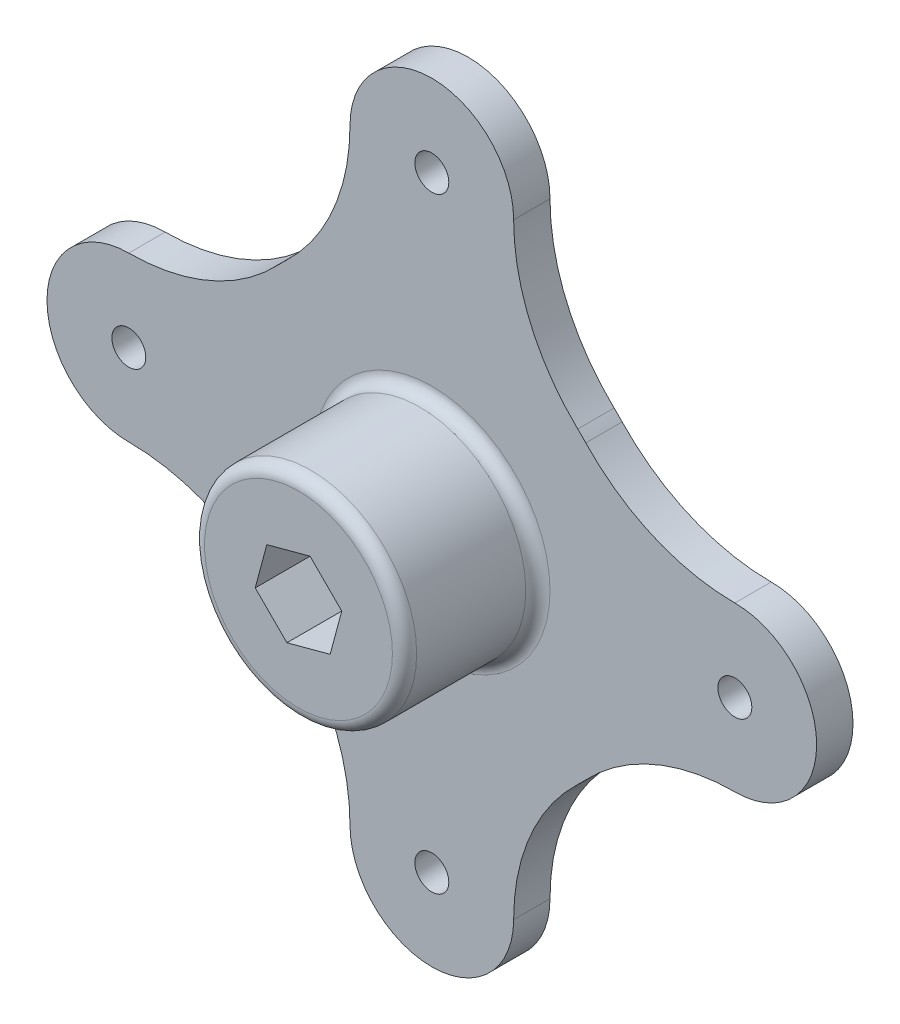
SolidWorks part; units mm, degrees
ref_plane "Front Plane" through (0, 0, 0) normal (0, 0, 1) x (1, 0, 0)
ref_plane "Top Plane" through (0, 0, 0) normal (0, 1, 0) x (1, 0, 0)
ref_plane "Right Plane" through (0, 0, 0) normal (1, 0, 0) x (0, 0, -1)
sketch "Sketch1" plane through (0, 0, 0) normal (0, 0, 1) x (1, 0, 0)
  line L0 (0, 0) -> (9.439, 9.439) construction
  line L1 (2.6128, -2.6128) -> (3.5691, 0.9563)
  line L2 (3.5691, 0.9563) -> (0.9563, 3.5691)
  line L3 (0.9563, 3.5691) -> (-2.6128, 2.6128)
  line L4 (-2.6128, 2.6128) -> (-3.5691, -0.9563)
  line L5 (-3.5691, -0.9563) -> (-0.9563, -3.5691)
  line L6 (-0.9563, -3.5691) -> (2.6128, -2.6128)
  line L7 (0, 0) -> (10.3087, 0) construction
  circle A0 centre (0, 0) radius 3.2 construction
  point P1 (1.8475, 3.2)
  point P11 (0, 0)
  point P12 (2.9055, -2.2829)
  dimension "D1" = 6.4
  dimension "D2" = 45
sketch "Sketch2" plane through (0, 0, 0) normal (0, 0, 1) x (1, 0, 0)
  circle A0 centre (0, 0) radius 8.75
  dimension "D1" = 17.5
extrude "Boss-Extrude1" add sketch "Sketch2" along normal blind 14
sketch "Sketch3" plane through (0, 0, 0) normal (0, 0, 1) x (1, 0, 0)
  circle A0 centre (0, 25) radius 1.4
  arc A1 (6.75, 25) -> (-6.75, 25) centre (0, 25) ccw
  circle A2 centre (0, 0) radius 17.5 construction
  arc A3 (-6.75, 25) -> (-12.0384, 12.7015) centre (-23.6948, 25) cw
  arc A4 (6.75, 25) -> (12.0384, 12.7015) centre (23.6948, 25) ccw
  arc A5 (-6.75, 25) -> (6.75, 25) centre (0, 25) ccw construction
  arc A6 (-25, 6.75) -> (-12.7015, 12.0384) centre (-25, 23.6948) ccw
  circle A7 centre (-25, 0) radius 1.4
  arc A8 (-25, 6.75) -> (-25, -6.75) centre (-25, 0) ccw
  arc A9 (-25, -6.75) -> (-12.7015, -12.0384) centre (-25, -23.6948) cw
  arc A10 (-6.75, -25) -> (-12.0384, -12.7015) centre (-23.6948, -25) ccw
  circle A11 centre (0, -25) radius 1.4
  arc A12 (-6.75, -25) -> (6.75, -25) centre (0, -25) ccw
  arc A13 (6.75, -25) -> (12.0384, -12.7015) centre (23.6948, -25) cw
  arc A14 (25, -6.75) -> (12.7015, -12.0384) centre (25, -23.6948) ccw
  circle A15 centre (25, 0) radius 1.4
  arc A16 (25, -6.75) -> (25, 6.75) centre (25, 0) ccw
  arc A17 (25, 6.75) -> (12.7015, 12.0384) centre (25, 23.6948) cw
  arc A18 (-12.7015, 12.0384) -> (-12.0384, 12.7015) centre (0, 0) cw
  arc A19 (12.0384, 12.7015) -> (12.7015, 12.0384) centre (0, 0) cw
  arc A20 (12.7015, -12.0384) -> (12.0384, -12.7015) centre (0, 0) cw
  arc A21 (-12.0384, -12.7015) -> (-12.7015, -12.0384) centre (0, 0) cw
  point P38 (0, 0)
  dimension "D1" = 35
  dimension "D2" = 13.5
  dimension "D4" = 2.8
  dimension "D3" = 25
  dimension "D5" = 4
extrude "Boss-Extrude2" add sketch "Sketch3" along normal blind 3 contours A21 A10 A12 A13 A20 A14 A16 A17 A19 A4 A1 A3 A18 A6 A8 A9 A15 A11 A7 A0
fillet "Fillet1" radius 1 2 edges at (8.75, 0, 3) (8.75, 0, 14)
extrude "Cut-Extrude2" cut sketch "Sketch1" along normal up to next
